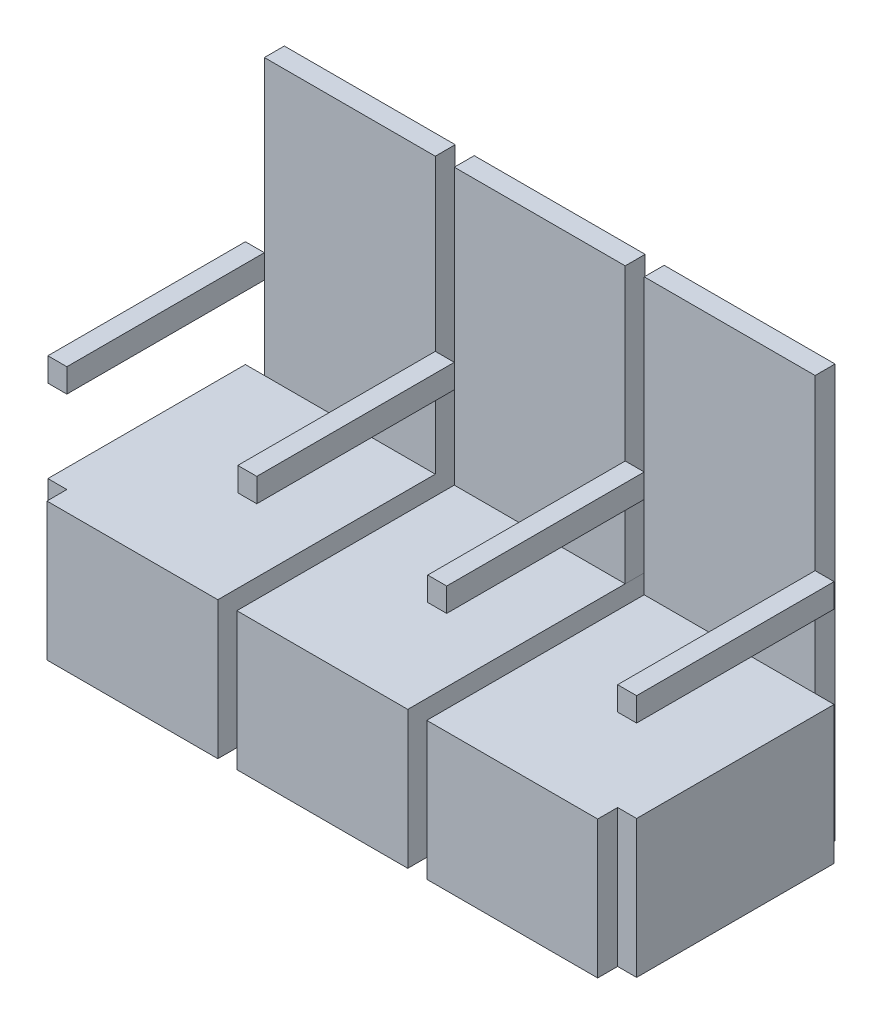
SolidWorks part; units mm, degrees
ref_plane "Front Plane" through (0, 0, 0) normal (0, 0, 1) x (1, 0, 0)
ref_plane "Top Plane" through (0, 0, 0) normal (0, 1, 0) x (1, 0, 0)
ref_plane "Right Plane" through (0, 0, 0) normal (1, 0, 0) x (0, 0, -1)
sketch "Sketch1" plane through (0, 0, 0) normal (0, 1, 0) x (1, 0, 0)
  line L0 (0, -55) -> (0, 55) construction
  line L13 (-787.4, 264.16) -> (-736.6, 264.16)
  line L14 (-736.6, 317.5) -> (-279.4, 317.5)
  line L15 (-787.4, 264.16) -> (-787.4, -264.16)
  line L16 (-736.6, -317.5) -> (-279.4, -317.5)
  line L17 (-279.4, 317.5) -> (-279.4, -317.5)
  line L18 (279.4, -317.5) -> (736.6, -317.5)
  line L19 (279.4, -317.5) -> (279.4, 317.5)
  line L20 (279.4, 317.5) -> (736.6, 317.5)
  line L21 (787.4, -264.16) -> (787.4, 264.16)
  line L22 (-736.6, 264.16) -> (-736.6, 317.5)
  line L23 (736.6, 264.16) -> (736.6, 317.5)
  line L24 (787.4, 264.16) -> (736.6, 264.16)
  line L25 (-55, 0) -> (55, 0) construction
  line L26 (736.6, -264.16) -> (736.6, -317.5)
  line L27 (-736.6, -264.16) -> (-736.6, -317.5)
  line L28 (-787.4, -264.16) -> (-736.6, -264.16)
  line L29 (787.4, -264.16) -> (736.6, -264.16)
  line L31 (-228.6, 317.5) -> (228.6, 317.5)
  line L32 (-228.6, 317.5) -> (-228.6, -317.5)
  line L33 (-228.6, -317.5) -> (228.6, -317.5)
  line L34 (228.6, 317.5) -> (228.6, -317.5)
  point P8 (-279.4, 0)
  point P9 (279.4, 0)
  point P30 (0, 317.5)
  dimension "D1" = 1574.8
  dimension "D2" = 50.8
  dimension "D3" = 50.8
  dimension "D4" = 53.34
  dimension "D5" = 635
  dimension "D6" = 50.8
  dimension "D7" = 457.2
extrude "Boss-Extrude1" add sketch "Sketch1" along normal blind 368.3
sketch "Sketch2" plane through (0, 368.3, 0) normal (0, 1, 0) x (1, 0, 0)
  line L0 (0, -202.565) -> (0, 202.565) construction
  line L1 (-736.6, 264.16) -> (-279.4, 264.16)
  line L2 (-736.6, 264.16) -> (-736.6, 317.5)
  line L3 (-736.6, 317.5) -> (-279.4, 317.5)
  line L4 (-279.4, 264.16) -> (-279.4, 317.5)
  line L5 (736.6, 317.5) -> (279.4, 317.5)
  line L6 (279.4, 264.16) -> (279.4, 317.5)
  line L7 (736.6, 264.16) -> (279.4, 264.16)
  line L8 (736.6, 264.16) -> (736.6, 317.5)
  line L9 (228.6, -317.5) -> (228.6, 317.5) construction
  line L10 (-228.6, 317.5) -> (228.6, 317.5)
  line L11 (-228.6, 317.5) -> (-228.6, 264.16)
  line L12 (-228.6, 264.16) -> (228.6, 264.16)
  line L13 (228.6, 317.5) -> (228.6, 264.16)
extrude "Boss-Extrude2" add sketch "Sketch2" along normal blind 736.6
sketch "Sketch3" plane through (0, 0, -264.16) normal (0, 0, 1) x (1, 0, 0)
  line L0 (-736.6, 1104.9) -> (-736.6, 368.3) construction
  line L1 (-736.6, 589.28) -> (-787.4, 589.28)
  line L2 (-736.6, 589.28) -> (-736.6, 652.78)
  line L3 (-736.6, 652.78) -> (-787.4, 652.78)
  line L4 (-787.4, 589.28) -> (-787.4, 652.78)
  line L5 (-787.4, 368.3) -> (-736.6, 368.3) construction
  line L6 (0, -349.25) -> (0, 349.25) construction
  line L7 (736.6, 652.78) -> (787.4, 652.78)
  line L8 (787.4, 589.28) -> (787.4, 652.78)
  line L9 (736.6, 589.28) -> (787.4, 589.28)
  line L10 (736.6, 589.28) -> (736.6, 652.78)
  line L11 (-279.4, 1104.9) -> (-279.4, 368.3) construction
  line L12 (-279.4, 589.28) -> (-228.6, 589.28)
  line L13 (-279.4, 589.28) -> (-279.4, 652.78)
  line L14 (-279.4, 652.78) -> (-228.6, 652.78)
  line L15 (279.4, 589.28) -> (279.4, 652.78)
  line L16 (279.4, 1104.9) -> (279.4, 368.3) construction
  line L17 (-228.6, 589.28) -> (-228.6, 652.78)
  line L18 (-228.6, 1104.9) -> (-228.6, 368.3) construction
  line L19 (228.6, 652.78) -> (228.6, 589.28)
  line L20 (228.6, 1104.9) -> (228.6, 368.3) construction
  line L21 (228.6, 652.78) -> (279.4, 652.78)
  line L22 (228.6, 589.28) -> (279.4, 589.28)
  dimension "D1" = 63.5
  dimension "D2" = 220.98
extrude "Boss-Extrude3" add sketch "Sketch3" along normal up to surface (528.32 mm away) separate body up to face at (-762, 184.15, 264.16)
